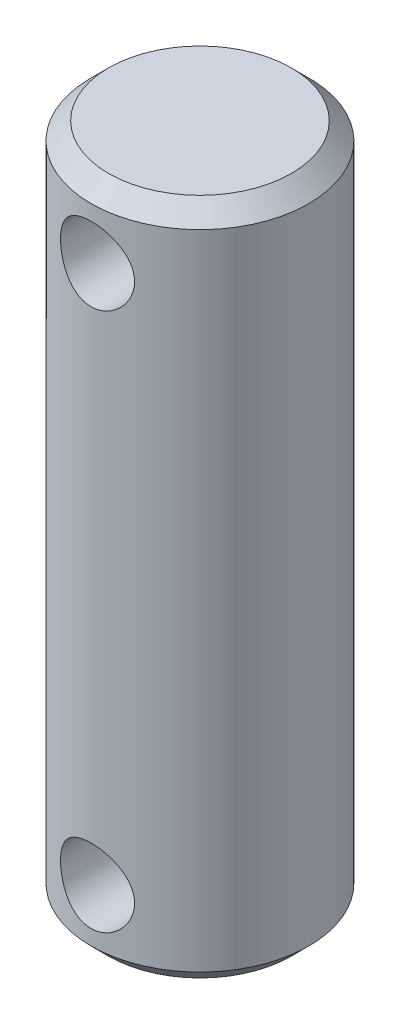
SolidWorks part; units mm, degrees
material "AISI 1045 Aço, trefilado"
ref_plane "Plano frontal" through (0, 0, 0) normal (0, 0, 1) x (1, 0, 0)
ref_plane "Plano superior" through (0, 0, 0) normal (0, 1, 0) x (1, 0, 0)
ref_plane "Plano direito" through (0, 0, 0) normal (1, 0, 0) x (0, 0, -1)
sketch "Esboço1" plane through (0, 0, 0) normal (0, 1, 0) x (1, 0, 0)
  circle A0 centre (0, 0) radius 12.5
  dimension "D1" = 25
extrude "Ressalto-extrusão1" add sketch "Esboço1" along normal mid plane 77.82
chamfer "Chanfro1" distance 2 angle 45 2 edges at (0, -38.91, 12.5) (0, 38.91, 12.5)
sketch "Esboço2" plane through (0, 0, 0) normal (0, 0, 1) x (1, 0, 0)
  line L0 (0, 38.91) -> (0, 30.91) construction
  line L1 (10.5, 38.91) -> (-10.5, 38.91) construction
  line L2 (0, -38.91) -> (0, -30.91) construction
  line L3 (-10.5, -38.91) -> (10.5, -38.91) construction
  circle A0 centre (0, 30.91) radius 4.25
  circle A1 centre (0, -30.91) radius 4.25
  dimension "D1" = 8.5
  dimension "D2" = 61.82
extrude "Corte-extrusão1" cut sketch "Esboço2" against normal mid plane 86
